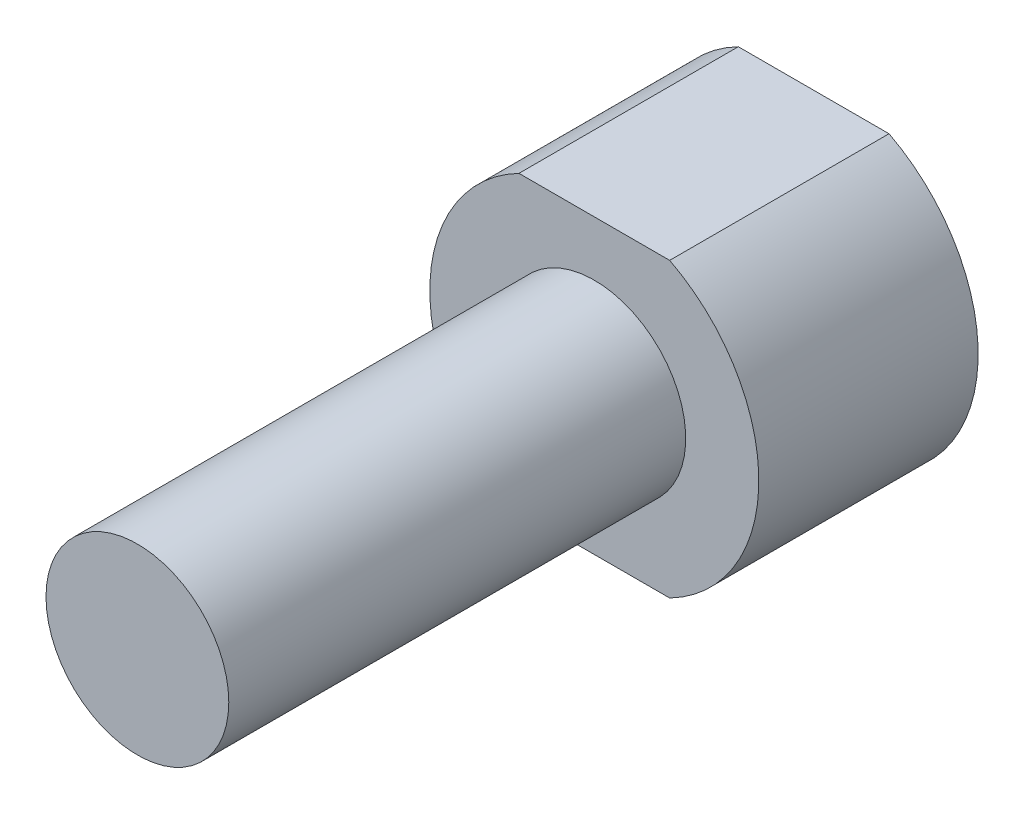
SolidWorks part; units mm, degrees
ref_plane "Plan de face" through (0, 0, 0) normal (0, 0, 1) x (1, 0, 0)
ref_plane "Plan de dessus" through (0, 0, 0) normal (0, 1, 0) x (1, 0, 0)
ref_plane "Plan de droite" through (0, 0, 0) normal (1, 0, 0) x (0, 0, -1)
sketch "Esquisse1" plane through (0, 0, 0) normal (0, 0, 1) x (1, 0, 0)
  line L0 (-12.5229, 8) -> (13.6047, 8) construction
  line L1 (13.6047, -8) -> (-12.5229, -8) construction
  line L2 (-12.5229, 0) -> (13.9382, 0) construction
  line L3 (-4.1231, 8) -> (4.1231, 8)
  line L4 (4.1231, -8) -> (-4.1231, -8)
  circle A0 centre (0, 0) radius 9 construction
  arc A1 (4.1231, 8) -> (4.1231, -8) centre (0, 0) cw
  arc A2 (-4.1231, 8) -> (-4.1231, -8) centre (0, 0) ccw
  dimension "D1" = 18
  dimension "D2" = 16
extrude "Boss.-Extru.1" add sketch "Esquisse1" along normal blind 12
sketch "Esquisse2" plane through (0, 0, 12) normal (0, 0, 1) x (1, 0, 0)
  circle A0 centre (0, 0) radius 5
  dimension "D1" = 10
extrude "Boss.-Extru.2" add sketch "Esquisse2" along normal blind 25
